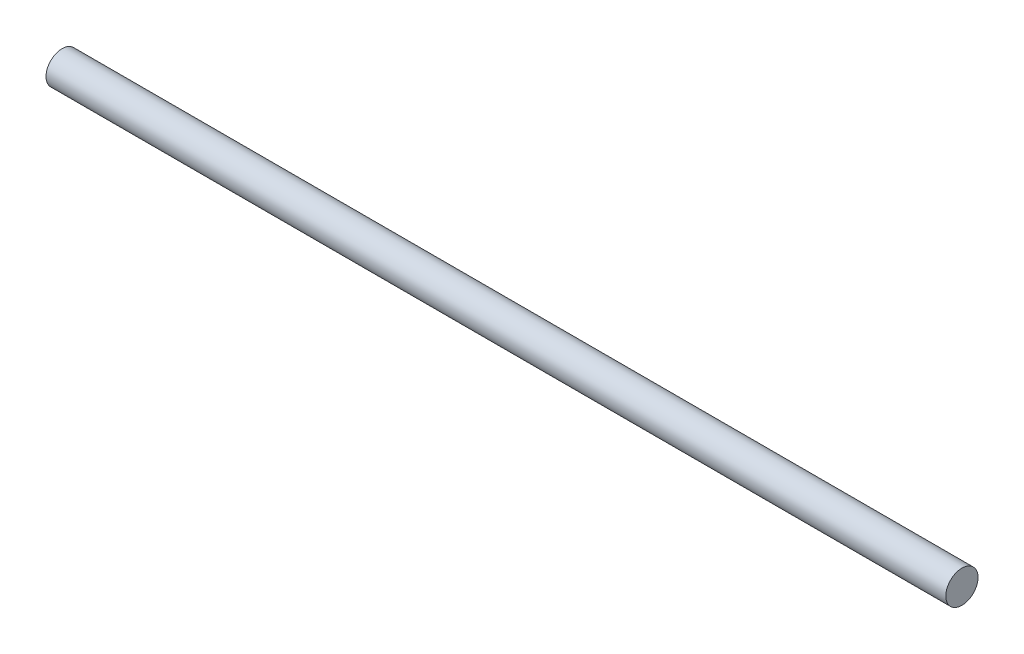
SolidWorks part; units mm, degrees
ref_plane "Front" through (0, 0, 0) normal (0, 0, 1) x (1, 0, 0)
ref_plane "Top" through (0, 0, 0) normal (0, 1, 0) x (1, 0, 0)
ref_plane "Right" through (0, 0, 0) normal (1, 0, 0) x (0, 0, -1)
sketch "Sketch2" plane through (0, 0, 0) normal (0, 0, 1) x (1, 0, 0)
  line L0 (0, 0) -> (14.2438, 0) construction
  line L1 (0, 0) -> (0, 3.9688)
  line L2 (0, 3.9688) -> (221.5224, 3.9688)
  line L3 (221.5224, 3.9688) -> (221.5224, 0)
  line L4 (221.5224, 0) -> (0, 0)
  line L5 (221.5224, 4.05) -> (221.5224, -4.05) construction
  dimension "D1" = 7.9375
revolve "Revolve1" add sketch "Sketch2" angle 360 about L0
